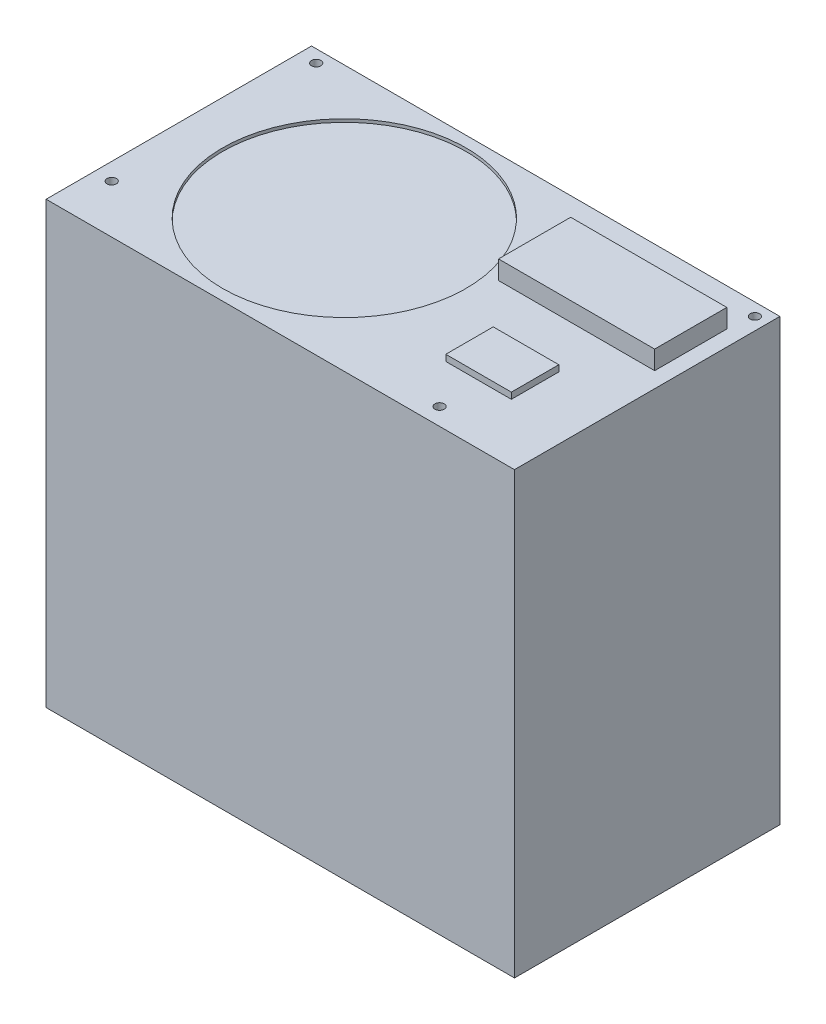
SolidWorks part; units mm, degrees
ref_plane "Plan de face" through (0, 0, 0) normal (0, 0, 1) x (1, 0, 0)
ref_plane "Plan de dessus" through (0, 0, 0) normal (0, 1, 0) x (1, 0, 0)
ref_plane "Plan de droite" through (0, 0, 0) normal (1, 0, 0) x (0, 0, -1)
sketch "Esquisse1" plane through (0, 0, 0) normal (0, 0, 1) x (1, 0, 0)
  line L1 (0, 0) -> (150, 0)
  line L2 (0, 0) -> (0, 141)
  line L3 (0, 141) -> (150, 141)
  line L4 (150, 0) -> (150, 141)
  dimension "D1" = 150
  dimension "D2" = 141
extrude "Boss.-Extru.1" add sketch "Esquisse1" along normal blind 85
sketch "Esquisse2" plane through (0, 141, 0) normal (0, 1, 0) x (1, 0, 0)
  line L0 (150, -85) -> (0, -85) construction
  line L1 (130, -66) -> (109, -66)
  line L2 (130, -66) -> (130, -50.8)
  line L3 (130, -50.8) -> (109, -50.8)
  line L4 (109, -66) -> (109, -50.8)
  line L6 (150, -85) -> (150, 0) construction
  dimension "D1" = 19
  dimension "D2" = 15.2
  dimension "D3" = 21
  dimension "D4" = 20
extrude "Boss.-Extru.2" add sketch "Esquisse2" along normal blind 2
sketch "Esquisse3" plane through (0, 141, 0) normal (0, 1, 0) x (1, 0, 0)
  line L0 (150, -85) -> (150, 0) construction
  line L1 (145, -35.11) -> (95, -35.11)
  line L2 (145, -35.11) -> (145, -12)
  line L3 (145, -12) -> (95, -12)
  line L4 (95, -35.11) -> (95, -12)
  line L5 (150, 0) -> (0, 0) construction
  dimension "D1" = 50
  dimension "D2" = 23.11
  dimension "D3" = 5
  dimension "D4" = 12
extrude "Boss.-Extru.3" add sketch "Esquisse3" along normal blind 6
sketch "Esquisse4" plane through (0, 141, 0) normal (0, 1, 0) x (1, 0, 0)
  line L2 (150, -42.5) -> (0, -42.5) construction
  line L3 (150, -85) -> (150, 0) construction
  line L4 (0, -85) -> (0, 0) construction
  circle A0 centre (53, -42.5) radius 39
  point P8 (0, 0)
  dimension "D1" = 78
  dimension "D2" = 53
extrude "Enlèv. mat.-Extru.1" cut sketch "Esquisse4" against normal blind 1
sketch "Esquisse5" plane through (0, 141, 0) normal (0, 1, 0) x (1, 0, 0)
  line L0 (150, -85) -> (150, 0) construction
  line L1 (150, -85) -> (0, -85) construction
  line L2 (0, -85) -> (0, 0) construction
  line L3 (150, 0) -> (0, 0) construction
  circle A0 centre (120.5, -79.5) radius 1.5
  circle A1 centre (5.5, -69.5) radius 1.5
  circle A2 centre (5.5, -4) radius 1.5
  circle A3 centre (146, -4) radius 1.5
  point P14 (0, 0)
  point P17 (0, 0)
  dimension "D1" = 3
  dimension "D5" = 15.5
  dimension "D2" = 29.5
  dimension "D3" = 5.5
  dimension "D4" = 5.5
  dimension "D6" = 4
  dimension "D7" = 4
extrude "Enlèv. mat.-Extru.2" cut sketch "Esquisse5" against normal blind 5
sketch "Esquisse6" plane through (0, 0, 0) normal (0, -1, 0) x (-1, 0, 0)
  line L0 (0, -85) -> (0, 0) construction
  line L1 (0, 0) -> (-150, 0) construction
  circle A0 centre (-12.5, -18.5) radius 12.5
  dimension "D1" = 25
  dimension "D2" = 18.5
extrude "Boss.-Extru.4" add sketch "Esquisse6" along normal blind 5
